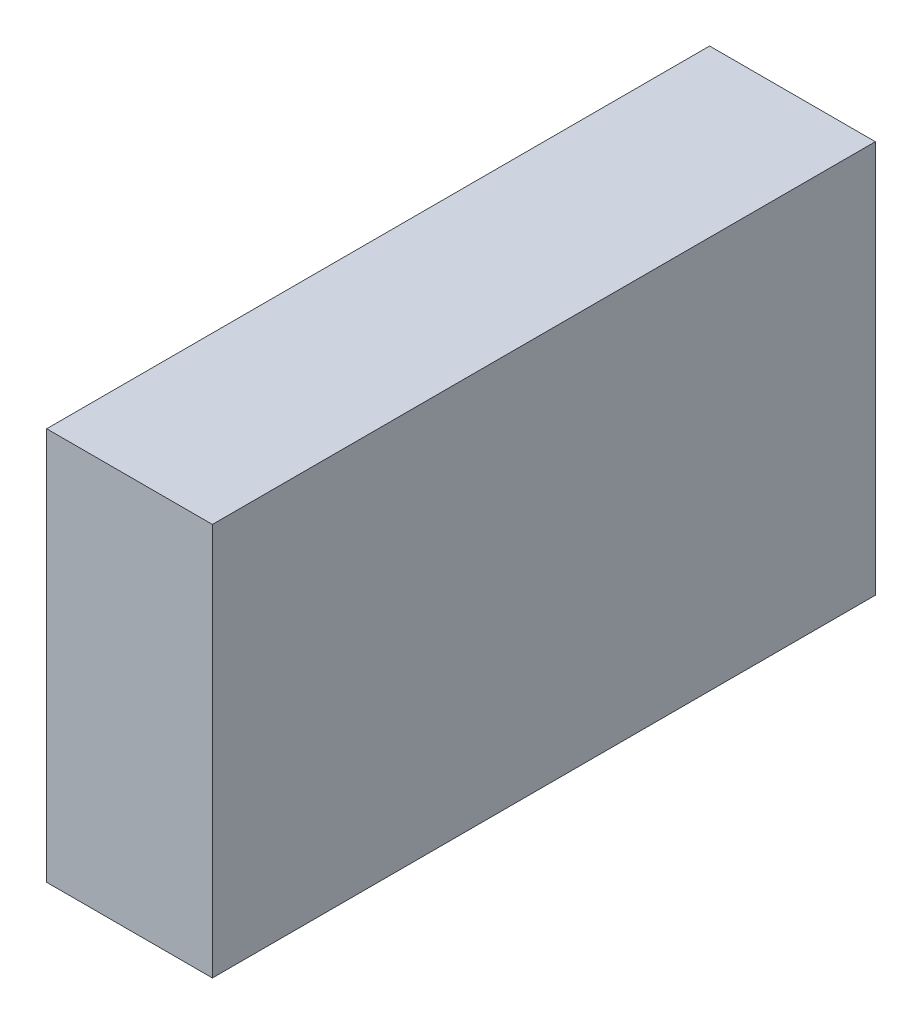
SolidWorks part; units mm, degrees
ref_plane "Front Plane" through (0, 0, 0) normal (0, 0, 1) x (1, 0, 0)
ref_plane "Top Plane" through (0, 0, 0) normal (0, 1, 0) x (1, 0, 0)
ref_plane "Right Plane" through (0, 0, 0) normal (1, 0, 0) x (0, 0, -1)
sketch "Sketch1" plane through (0, 0, 0) normal (1, 0, 0) x (0, 0, -1)
  line L1 (0, 0) -> (40, 0)
  line L2 (0, 0) -> (0, 23.7)
  line L3 (0, 23.7) -> (40, 23.7)
  line L4 (40, 0) -> (40, 23.7)
extrude "Boss-Extrude1" add sketch "Sketch1" against normal blind 10
